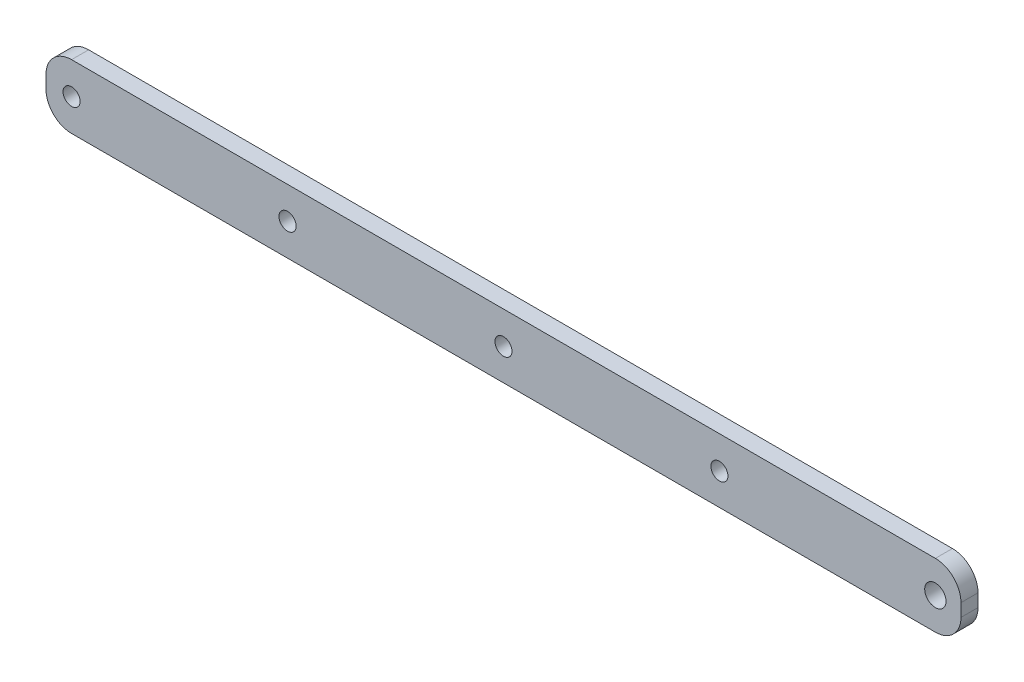
SolidWorks part; units mm, degrees
material "ABS PC"
ref_plane "Front Plane" through (0, 0, 0) normal (0, 0, 1) x (1, 0, 0)
ref_plane "Top Plane" through (0, 0, 0) normal (0, 1, 0) x (1, 0, 0)
ref_plane "Right Plane" through (0, 0, 0) normal (1, 0, 0) x (0, 0, -1)
sketch "Sketch1" plane through (0, 0, 0) normal (0, 0, 1) x (1, 0, 0)
  line L1 (7.62, 0) -> (264.922, 0)
  line L2 (0, 7.62) -> (0, 11.43)
  line L3 (7.62, 19.05) -> (264.922, 19.05)
  line L4 (272.542, 7.62) -> (272.542, 11.43)
  circle A0 centre (264.922, 9.525) radius 3.175
  circle A1 centre (7.62, 9.525) radius 2.54
  arc A2 (264.922, 0) -> (272.542, 7.62) centre (264.922, 7.62) ccw
  arc A3 (7.62, 0) -> (0, 7.62) centre (7.62, 7.62) cw
  arc A4 (264.922, 19.05) -> (272.542, 11.43) centre (264.922, 11.43) cw
  arc A5 (0, 11.43) -> (7.62, 19.05) centre (7.62, 11.43) cw
  circle A6 centre (71.9455, 9.525) radius 2.5586
  circle A7 centre (136.271, 9.398) radius 2.54
  circle A8 centre (200.5965, 9.398) radius 2.54
  point P13 (0, 0)
  dimension "D3" = 5.08
  dimension "D4" = 6.35
  dimension "D9" = 7.62
  dimension "D10" = 5.1173
  dimension "D11" = 5.08
  dimension "D12" = 5.08
  dimension "D14" = 9.525
  dimension "D1" = 257.302
  dimension "D2" = 19.05
  dimension "D5" = 9.525
  dimension "D6" = 7.62
  dimension "D7" = 7.62
  dimension "D8" = 9.525
  dimension "D13" = 64.3255
  dimension "D15" = 64.3255
  dimension "D16" = 9.652
  dimension "D17" = 64.3255
  dimension "D18" = 9.652
extrude "Boss-Extrude1" add sketch "Sketch1" along normal blind 5.08
